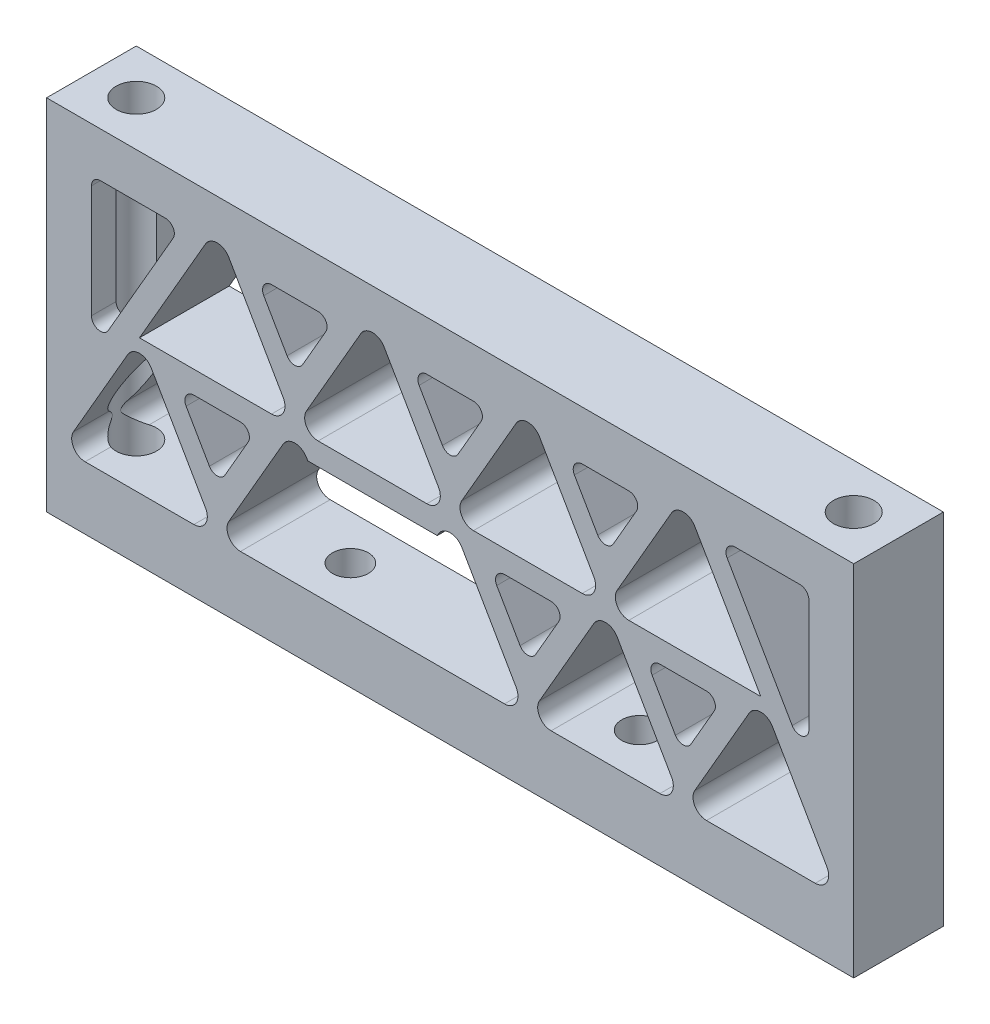
SolidWorks part; units mm, degrees
ref_plane "Front Plane" through (0, 0, 0) normal (0, 0, 1) x (1, 0, 0)
ref_plane "Top Plane" through (0, 0, 0) normal (0, 1, 0) x (1, 0, 0)
ref_plane "Right Plane" through (0, 0, 0) normal (1, 0, 0) x (0, 0, -1)
sketch "Sketch1" plane through (0, 0, 0) normal (0, 1, 0) x (1, 0, 0)
  line L1 (0, 0) -> (90, 0)
  line L2 (0, 0) -> (0, 10)
  line L3 (0, 10) -> (90, 10)
  line L4 (90, 0) -> (90, 10)
  dimension "D1" = 90
  dimension "D2" = 10
extrude "Boss-Extrude1" add sketch "Sketch1" along normal blind 40
sketch "Sketch2" plane through (0, 0, 0) normal (0, 0, 1) x (1, 0, 0)
  line L6 (0, 7) -> (90, 7) construction
  line L7 (0, 40) -> (0, 0) construction
  line L8 (90, 40) -> (90, 0) construction
  line L9 (0, 0) -> (90, 0) construction
  line L10 (26.3805, 19.75) -> (20.3183, 9.25)
  line L11 (9.0599, 19.75) -> (2.9978, 9.25)
  line L12 (4.2968, 7) -> (16.4212, 7)
  line L13 (17.7202, 9.25) -> (11.658, 19.75)
  line L14 (21.6173, 7) -> (33.7417, 7)
  line L15 (35.0407, 9.25) -> (28.9785, 19.75)
  line L16 (43.701, 19.75) -> (37.6388, 9.25)
  line L17 (38.9378, 7) -> (51.0622, 7)
  line L18 (52.3612, 9.25) -> (46.299, 19.75)
  line L19 (61.0215, 19.75) -> (54.9593, 9.25)
  line L20 (56.2583, 7) -> (68.3827, 7)
  line L21 (69.6817, 9.25) -> (63.6195, 19.75)
  line L22 (78.342, 19.75) -> (72.2798, 9.25)
  line L23 (73.5788, 7) -> (85.7032, 7)
  line L24 (87.0022, 9.25) -> (80.9401, 19.75)
  line L25 (45, 40) -> (45, 0) construction
  line L26 (0, 40) -> (90, 40) construction
  line L27 (10.359, 22) -> (79.641, 22) construction
  line L28 (35.0407, 34.75) -> (28.9785, 24.25)
  line L29 (17.7202, 34.75) -> (10.359, 22)
  line L30 (10.359, 22) -> (25.0814, 22)
  line L31 (26.3805, 24.25) -> (20.3183, 34.75)
  line L32 (30.2776, 22) -> (42.4019, 22)
  line L33 (43.701, 24.25) -> (37.6388, 34.75)
  line L34 (52.3612, 34.75) -> (46.299, 24.25)
  line L35 (47.5981, 22) -> (59.7224, 22)
  line L36 (61.0215, 24.25) -> (54.9593, 34.75)
  line L37 (69.6817, 34.75) -> (63.6195, 24.25)
  line L38 (64.9186, 22) -> (79.641, 22)
  line L39 (79.641, 22) -> (72.2798, 34.75)
  circle A0 centre (10.359, 12) radius 5 construction
  circle A1 centre (19.0192, 27) radius 5 construction
  arc A2 (17.7202, 34.75) -> (20.3183, 34.75) centre (19.0192, 34) cw
  arc A3 (35.0407, 34.75) -> (37.6388, 34.75) centre (36.3397, 34) cw
  arc A4 (52.3612, 34.75) -> (54.9593, 34.75) centre (53.6603, 34) cw
  arc A5 (69.6817, 34.75) -> (72.2798, 34.75) centre (70.9808, 34) cw
  arc A6 (78.342, 19.75) -> (80.9401, 19.75) centre (79.641, 19) cw
  arc A7 (85.7032, 7) -> (87.0022, 9.25) centre (85.7032, 8.5) ccw
  arc A8 (61.0215, 19.75) -> (63.6195, 19.75) centre (62.3205, 19) cw
  arc A9 (68.3827, 7) -> (69.6817, 9.25) centre (68.3827, 8.5) ccw
  arc A10 (43.701, 19.75) -> (46.299, 19.75) centre (45, 19) cw
  arc A11 (51.0622, 7) -> (52.3612, 9.25) centre (51.0622, 8.5) ccw
  arc A12 (26.3805, 19.75) -> (28.9785, 19.75) centre (27.6795, 19) cw
  arc A13 (33.7417, 7) -> (35.0407, 9.25) centre (33.7417, 8.5) ccw
  arc A14 (9.0599, 19.75) -> (11.658, 19.75) centre (10.359, 19) cw
  arc A15 (16.4212, 7) -> (17.7202, 9.25) centre (16.4212, 8.5) ccw
  arc A16 (2.9978, 9.25) -> (4.2968, 7) centre (4.2968, 8.5) ccw
  arc A17 (59.7224, 22) -> (61.0215, 24.25) centre (59.7224, 23.5) ccw
  arc A18 (42.4019, 22) -> (43.701, 24.25) centre (42.4019, 23.5) ccw
  arc A19 (25.0814, 22) -> (26.3805, 24.25) centre (25.0814, 23.5) ccw
  arc A20 (72.2798, 9.25) -> (73.5788, 7) centre (73.5788, 8.5) ccw
  arc A21 (54.9593, 9.25) -> (56.2583, 7) centre (56.2583, 8.5) ccw
  arc A22 (37.6388, 9.25) -> (38.9378, 7) centre (38.9378, 8.5) ccw
  arc A23 (20.3183, 9.25) -> (21.6173, 7) centre (21.6173, 8.5) ccw
  arc A24 (63.6195, 24.25) -> (64.9186, 22) centre (64.9186, 23.5) ccw
  arc A25 (46.299, 24.25) -> (47.5981, 22) centre (47.5981, 23.5) ccw
  arc A26 (28.9785, 24.25) -> (30.2776, 22) centre (30.2776, 23.5) ccw
  point P64 (45, 22)
  point P69 (27.6795, 22)
  point P77 (19.0192, 7)
  point P80 (1.6987, 7)
  point P87 (27.6795, 22)
  point P96 (19.0192, 7)
  point P103 (27.6795, 22)
  dimension "D5" = 1.5
  dimension "D6" = 1.5
  dimension "D7" = 1.5
  dimension "D8" = 1.5
  dimension "D1" = 7
  dimension "D3" = 15
  dimension "D4" = 4
  dimension "D2" = 5
extrude "Cut-Extrude1" cut sketch "Sketch2" against normal through all
sketch "Sketch3" plane through (0, 0, 0) normal (0, 0, 1) x (1, 0, 0)
  line L0 (10.359, 22) -> (25.0814, 22) construction
  line L1 (19.8853, 13.5) -> (22.4833, 18)
  line L2 (21.6173, 19.5) -> (16.4212, 19.5)
  line L3 (15.5551, 18) -> (18.1532, 13.5)
  line L6 (26.3805, 19.75) -> (20.3183, 9.25) construction
  line L7 (17.7202, 9.25) -> (11.658, 19.75) construction
  line L8 (37.2053, 13.5) -> (39.8033, 18)
  line L9 (38.9373, 19.5) -> (33.7412, 19.5)
  line L10 (32.8751, 18) -> (35.4732, 13.5)
  line L11 (54.5253, 13.5) -> (57.1233, 18)
  line L12 (56.2573, 19.5) -> (51.0612, 19.5)
  line L13 (50.1951, 18) -> (52.7932, 13.5)
  line L14 (71.8453, 13.5) -> (74.4433, 18)
  line L15 (73.5773, 19.5) -> (68.3812, 19.5)
  line L16 (67.5151, 18) -> (70.1132, 13.5)
  line L17 (35.0407, 9.25) -> (28.9785, 19.75) construction
  line L18 (26.3805, 24.25) -> (20.3183, 34.75) construction
  line L19 (28.5455, 28.5) -> (31.1436, 33)
  line L20 (30.2776, 34.5) -> (25.0814, 34.5)
  line L21 (24.2154, 33) -> (26.8135, 28.5)
  line L22 (35.0407, 34.75) -> (28.9785, 24.25) construction
  line L23 (45.8655, 28.5) -> (48.4636, 33)
  line L24 (47.5976, 34.5) -> (42.4014, 34.5)
  line L25 (41.5354, 33) -> (44.1335, 28.5)
  line L26 (63.1855, 28.5) -> (65.7836, 33)
  line L27 (64.9176, 34.5) -> (59.7214, 34.5)
  line L28 (58.8554, 33) -> (61.4535, 28.5)
  line L29 (43.701, 24.25) -> (37.6388, 34.75) construction
  circle A0 centre (19.0192, 17) radius 2.5 construction
  circle A1 centre (27.6795, 32) radius 2.5 construction
  arc A2 (68.3812, 19.5) -> (67.5151, 18) centre (68.3812, 18.5) ccw
  arc A3 (74.4433, 18) -> (73.5773, 19.5) centre (73.5773, 18.5) ccw
  arc A4 (71.8453, 13.5) -> (70.1132, 13.5) centre (70.9792, 14) cw
  arc A5 (59.7214, 34.5) -> (58.8554, 33) centre (59.7214, 33.5) ccw
  arc A6 (65.7836, 33) -> (64.9176, 34.5) centre (64.9176, 33.5) ccw
  arc A7 (63.1855, 28.5) -> (61.4535, 28.5) centre (62.3195, 29) cw
  arc A8 (25.0814, 34.5) -> (24.2154, 33) centre (25.0814, 33.5) ccw
  arc A9 (31.1436, 33) -> (30.2776, 34.5) centre (30.2776, 33.5) ccw
  arc A10 (28.5455, 28.5) -> (26.8135, 28.5) centre (27.6795, 29) cw
  arc A11 (42.4014, 34.5) -> (41.5354, 33) centre (42.4014, 33.5) ccw
  arc A12 (48.4636, 33) -> (47.5976, 34.5) centre (47.5976, 33.5) ccw
  arc A13 (45.8655, 28.5) -> (44.1335, 28.5) centre (44.9995, 29) cw
  arc A14 (51.0612, 19.5) -> (50.1951, 18) centre (51.0612, 18.5) ccw
  arc A15 (57.1233, 18) -> (56.2573, 19.5) centre (56.2573, 18.5) ccw
  arc A16 (54.5253, 13.5) -> (52.7932, 13.5) centre (53.6592, 14) cw
  arc A17 (33.7412, 19.5) -> (32.8751, 18) centre (33.7412, 18.5) ccw
  arc A18 (39.8033, 18) -> (38.9373, 19.5) centre (38.9373, 18.5) ccw
  arc A19 (37.2053, 13.5) -> (35.4732, 13.5) centre (36.3392, 14) cw
  arc A20 (16.4212, 19.5) -> (15.5551, 18) centre (16.4212, 18.5) ccw
  arc A21 (22.4833, 18) -> (21.6173, 19.5) centre (21.6173, 18.5) ccw
  arc A22 (19.8853, 13.5) -> (18.1532, 13.5) centre (19.0192, 14) cw
  dimension "D8" = 5
  dimension "D11" = 1
  dimension "D1" = 2.5
  dimension "D2" = 2.5
  dimension "D3" = 2.5
  dimension "D5" = 2.4996
  dimension "D6" = 2.5
  dimension "D7" = 2.5
  dimension "D10" = 2.4996
  dimension "D4" = 4
  dimension "D9" = 3
extrude "Cut-Extrude2" cut sketch "Sketch3" against normal through all
sketch "Sketch4" plane through (0, 0, 0) normal (0, 0, 1) x (1, 0, 0)
  line L0 (5, 21.45) -> (5, 34)
  line L4 (6, 35) -> (13.2457, 35)
  line L5 (14.1118, 33.5) -> (6.866, 20.95)
  line L6 (17.7202, 34.75) -> (10.359, 22) construction
  line L7 (0, 40) -> (0, 0) construction
  line L8 (0, 40) -> (90, 40) construction
  line L9 (45, 40) -> (45, 0) construction
  line L10 (0, 0) -> (90, 0) construction
  line L11 (84, 35) -> (76.7543, 35)
  line L12 (85, 21.45) -> (85, 34)
  line L13 (75.8882, 33.5) -> (83.134, 20.95)
  arc A0 (5, 34) -> (6, 35) centre (6, 34) cw
  arc A1 (13.2457, 35) -> (14.1118, 33.5) centre (13.2457, 34) cw
  arc A2 (5, 21.45) -> (6.866, 20.95) centre (6, 21.45) ccw
  arc A3 (85, 34) -> (84, 35) centre (84, 34) ccw
  arc A4 (76.7543, 35) -> (75.8882, 33.5) centre (76.7543, 34) ccw
  arc A5 (85, 21.45) -> (83.134, 20.95) centre (84, 21.45) cw
  dimension "D4" = 1
  dimension "D1" = 5
  dimension "D2" = 5
  dimension "D3" = 2.5
extrude "Cut-Extrude3" cut sketch "Sketch4" against normal through all
sketch "Sketch5" plane through (0, 40, 0) normal (0, 1, 0) x (1, 0, 0)
  line L0 (0, 10) -> (0, 0) construction
  line L1 (90, 0) -> (90, 10) construction
  line L2 (0, 0) -> (90, 0) construction
  circle A0 centre (5, 5) radius 2.25
  circle A1 centre (85, 5) radius 2.25
  point P8 (90, 5)
  dimension "D4" = 4.5
  dimension "D1" = 5
  dimension "D2" = 5
  dimension "D3" = 5
extrude "Cut-Extrude4" cut sketch "Sketch5" against normal up to next
sketch "Sketch6" plane through (0, 0, 0) normal (0, -1, 0) x (1, 0, 0)
  line L0 (45, 0) -> (45, -10) construction
  line L1 (0, 0) -> (90, 0) construction
  line L2 (90, -10) -> (0, -10) construction
  circle A0 centre (28.875, -5) radius 2
  circle A1 centre (61.125, -5) radius 2
  dimension "D1" = 4
  dimension "D2" = 4
  dimension "D3" = 5
  dimension "D4" = 32.25
extrude "Cut-Extrude5" cut sketch "Sketch6" against normal up to next
sketch "Sketch7" plane through (0, 0, 0) normal (0, 0, 1) x (1, 0, 0)
  line L0 (21.6173, 7) -> (33.7417, 7) construction
  line L1 (27.6795, 7) -> (45, 7)
  line L2 (27.6795, 7) -> (27.6795, 19.5)
  line L3 (27.6795, 19.5) -> (45, 19.5)
  line L4 (45, 7) -> (45, 19.5)
  line L5 (27.6795, 7) -> (27.6795, 20.5) construction
  line L6 (45, 7) -> (45, 20.5) construction
  line L7 (38.9378, 7) -> (51.0622, 7) construction
  line L8 (38.9373, 19.5) -> (33.7412, 19.5) construction
  arc A0 (28.9785, 19.75) -> (26.3805, 19.75) centre (27.6795, 19) ccw construction
  arc A1 (46.299, 19.75) -> (43.701, 19.75) centre (45, 19) ccw construction
extrude "Cut-Extrude6" cut sketch "Sketch7" against normal through all
